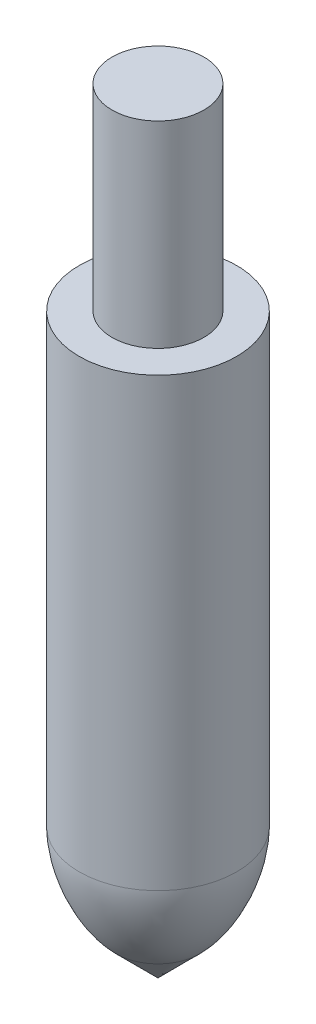
SolidWorks part; units mm, degrees
material "Brass"
ref_plane "Front Plane" through (0, 0, 0) normal (0, 0, 1) x (1, 0, 0)
ref_plane "Top Plane" through (0, 0, 0) normal (0, 1, 0) x (1, 0, 0)
ref_plane "Right Plane" through (0, 0, 0) normal (1, 0, 0) x (0, 0, -1)
sketch "Sketch1" plane through (0, 0, 0) normal (0, 0, 1) x (1, 0, 0)
  line L0 (0, 0) -> (0, 29.5)
  line L1 (0, 29.5) -> (1.75, 29.5)
  line L2 (1.75, 29.5) -> (1.75, 22)
  line L3 (1.75, 22) -> (3, 22)
  line L6 (3, 22) -> (3, 3)
  line L8 (3, 3) -> (0, 0)
  line L9 (0, 40.5915) -> (0, -10.1406) construction
  dimension "D1" = 29.5
  dimension "D2" = 45
  dimension "D3" = 3
  dimension "D4" = 1.75
  dimension "D5" = 19
revolve "Revolve1" add sketch "Sketch1" angle 360 about L9
sketch "Sketch2" plane through (0, 0, 0) normal (0, 0, 1) x (1, 0, 0)
  line L0 (3, 3) -> (3, 22) construction
  line L1 (0, 0) -> (3, 3) construction
  line L2 (3, 5) -> (3, 3)
  line L3 (3, 3) -> (1.5858, 1.5858)
  line L4 (0, 0) -> (0, 5.4596) construction
  spline S0 degree 3 poles (3, 5) (3, 3.8942) (2.4065, 2.4065) (1.5858, 1.5858) knots 0 0 0 0 1 1 1 1
  dimension "D1" = 2
  dimension "D2" = 2
revolve "Cut-Revolve1" cut sketch "Sketch2" angle 360 about L4
